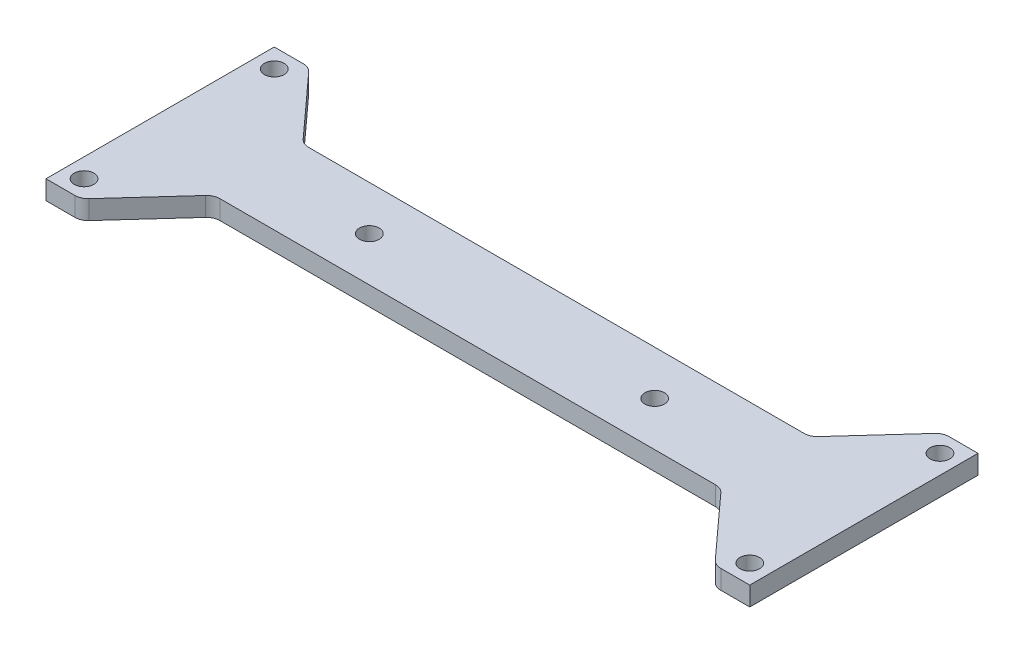
SolidWorks part; units mm, degrees
ref_plane "正面" through (0, 0, 0) normal (0, 0, 1) x (1, 0, 0)
ref_plane "平面" through (0, 0, 0) normal (0, 1, 0) x (1, 0, 0)
ref_plane "右側面" through (0, 0, 0) normal (1, 0, 0) x (0, 0, -1)
sketch "ｽｹｯﾁ1" plane through (0, 0, 0) normal (0, 1, 0) x (1, 0, 0)
  line L0 (-22.5, 0) -> (22.5, 0) construction
  line L1 (-55.5, 18) -> (55.5, 18)
  line L2 (-55.5, 18) -> (-55.5, -18)
  line L3 (-55.5, -18) -> (55.5, -18)
  line L4 (55.5, 18) -> (55.5, -18)
  line L5 (-55.5, 18) -> (55.5, -18) construction
  line L6 (-55.5, -18) -> (55.5, 18) construction
  line L7 (-52.5, 15) -> (52.5, 15) construction
  line L8 (-52.5, 15) -> (-52.5, -15) construction
  line L9 (-52.5, -15) -> (52.5, -15) construction
  line L10 (52.5, 15) -> (52.5, -15) construction
  line L11 (-52.5, 15) -> (52.5, -15) construction
  line L12 (-52.5, -15) -> (52.5, 15) construction
  circle A0 centre (-52.5, 15) radius 1.55
  circle A1 centre (-52.5, -15) radius 1.55
  circle A2 centre (52.5, -15) radius 1.55
  circle A3 centre (52.5, 15) radius 1.55
  circle A4 centre (-22.5, 0) radius 1.55
  circle A5 centre (22.5, 0) radius 1.55
  point P0 (0, 0)
  point P5 (0, 0)
  point P17 (0, 0)
  dimension "D5" = 3.1
  dimension "D7" = 3.1
  dimension "D1" = 111
  dimension "D2" = 36
  dimension "D3" = 105
  dimension "D4" = 30
  dimension "D6" = 45
extrude "ﾎﾞｽ - 押し出し1" add sketch "ｽｹｯﾁ1" along normal blind 3
sketch "ｽｹｯﾁ2" plane through (0, 3, 0) normal (0, 1, 0) x (1, 0, 0)
  line L0 (-50, 18) -> (-40, 7)
  line L1 (55.5, 18) -> (-55.5, 18) construction
  line L2 (-40, 7) -> (40, 7)
  line L3 (40, 7) -> (50, 18)
  line L4 (50, 18) -> (-50, 18)
  line L5 (0, -18) -> (0, 18) construction
  line L6 (-55.5, -18) -> (55.5, -18) construction
  line L7 (-55.5, 0) -> (55.5, 0) construction
  line L8 (-55.5, 18) -> (-55.5, -18) construction
  line L9 (55.5, -18) -> (55.5, 18) construction
  line L10 (50, -18) -> (-50, -18)
  line L11 (40, -7) -> (50, -18)
  line L12 (-40, -7) -> (40, -7)
  line L13 (-50, -18) -> (-40, -7)
  point P13 (0, 7)
  dimension "D1" = 100
  dimension "D2" = 7
  dimension "D3" = 80
extrude "ｶｯﾄ - 押し出し1" cut sketch "ｽｹｯﾁ2" against normal through all
fillet "ﾌｨﾚｯﾄ2" radius 2.1 8 edges at (50, 1.5, -18) (40, 1.5, -7) (50, 1.5, 18) (40, 1.5, 7) (-40, 1.5, 7) (-50, 1.5, 18) (-40, 1.5, -7) (-50, 1.5, -18)
